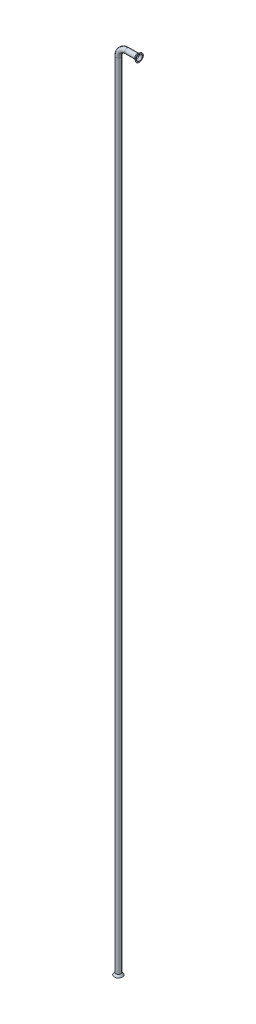
SolidWorks part; units mm, degrees
material "AISI 316 Annealed Stainless Steel Bar (SS)"
ref_plane "Front Plane" through (0, 0, 0) normal (0, 0, 1) x (1, 0, 0)
ref_plane "Top Plane" through (0, 0, 0) normal (0, 1, 0) x (1, 0, 0)
ref_plane "Right Plane" through (0, 0, 0) normal (1, 0, 0) x (0, 0, -1)
sketch "Sketch1" plane through (0, 0, 0) normal (0, 1, 0) x (1, 0, 0)
  circle A0 centre (0, 0) radius 3.175
  circle A1 centre (0, 0) radius 1.9304
  dimension "D1" = 6.35
  dimension "D2" = 1.2446
sketch "Sketch2" plane through (0, 0, 0) normal (0, 0, 1) x (1, 0, 0)
  line L0 (0, 0) -> (0, 1004.7224)
  line L1 (11.2776, 1016) -> (23.9776, 1016)
  arc A0 (0, 1004.7224) -> (11.2776, 1016) centre (11.2776, 1004.7224) cw
  dimension "D1" = 1016
  dimension "D2" = 12.7
  dimension "D3" = 23.9776
sweep "Sweep1" add profiles "Sketch1" path "Sketch2"
sketch "Sketch3" plane through (0, 0, 0) normal (0, -1, 0) x (1, 0, 0)
  circle A0 centre (0, 0) radius 3.175
  circle A1 centre (0, 0) radius 3.175 construction
extrude "Boss-Extrude1" add sketch "Sketch3" along normal blind 2.54 draft 37 draft outward yes
sketch "Sketch4" plane through (0, -2.54, 0) normal (0, -1, 0) x (1, 0, 0)
  line L0 (-3.175, 0) -> (-1.9304, 0) construction
  line L1 (-3.8444, 0) -> (-5.089, 0) construction
  circle A0 centre (0, 0) radius 3.8444
  circle A1 centre (0, 0) radius 3.175 construction
  circle A2 centre (0, 0) radius 1.9304 construction
  circle A3 centre (0, 0) radius 5.089 construction
extrude "Cut-Extrude1" cut sketch "Sketch4" against normal through all draft 37
sketch "Sketch5" plane through (23.9776, 0, 0) normal (1, 0, 0) x (0, 0, -1)
  circle A1 centre (0, 1016) radius 3.175
  circle A2 centre (0, 1016) radius 3.175 construction
  circle A3 centre (0, 1016) radius 3.175 construction
extrude "Boss-Extrude2" add sketch "Sketch5" along normal blind 2.54 draft 37 draft outward yes
sketch "Sketch6" plane through (26.5176, 0, 0) normal (1, 0, 0) x (0, 0, -1)
  line L0 (-3.8444, 1016) -> (-5.089, 1016) construction
  circle A0 centre (0, 1016) radius 3.8444
  circle A1 centre (0, 1016) radius 5.089 construction
  dimension "D1" = 1.2446
extrude "Cut-Extrude2" cut sketch "Sketch6" against normal through all draft 37
